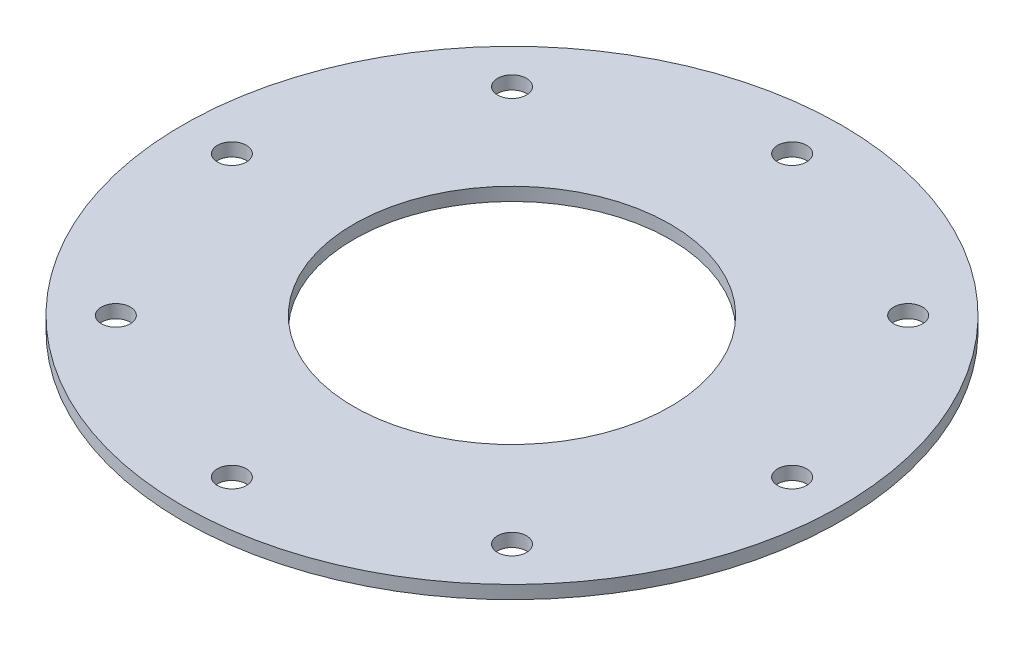
SolidWorks part; units mm, degrees
material "AISI 304"
ref_plane "Спереди" through (0, 0, 0) normal (0, 0, 1) x (1, 0, 0)
ref_plane "Сверху" through (0, 0, 0) normal (0, 1, 0) x (1, 0, 0)
ref_plane "Справа" through (0, 0, 0) normal (1, 0, 0) x (0, 0, -1)
sketch "Эскиз1" plane through (0, 0, 0) normal (0, 1, 0) x (1, 0, 0)
  line L0 (0, 0) -> (100, 0) construction
  circle A0 centre (0, 0) radius 100
  circle A1 centre (0, 0) radius 48
  circle A2 centre (0, 0) radius 85 construction
  circle A3 centre (85, 0) radius 4.4
  circle A4 centre (60.1041, -60.1041) radius 4.4
  circle A5 centre (0, -85) radius 4.4
  circle A6 centre (-60.1041, -60.1041) radius 4.4
  circle A7 centre (-85, 0) radius 4.4
  circle A8 centre (-60.1041, 60.1041) radius 4.4
  circle A9 centre (0, 85) radius 4.4
  circle A10 centre (60.1041, 60.1041) radius 4.4
  point P6 (84.9836, 0)
  dimension "D1" = 200
  dimension "D2" = 96
  dimension "D3" = 170
  dimension "D4" = 8.8
  dimension "D5" = 8
extrude "Бобышка-Вытянуть1" add sketch "Эскиз1" along normal blind 4
equation "\"Толщина фланца обоймы\"= 4мм"
equation "\"D1@Бобышка-Вытянуть1\"=\"Толщина фланца обоймы\""
